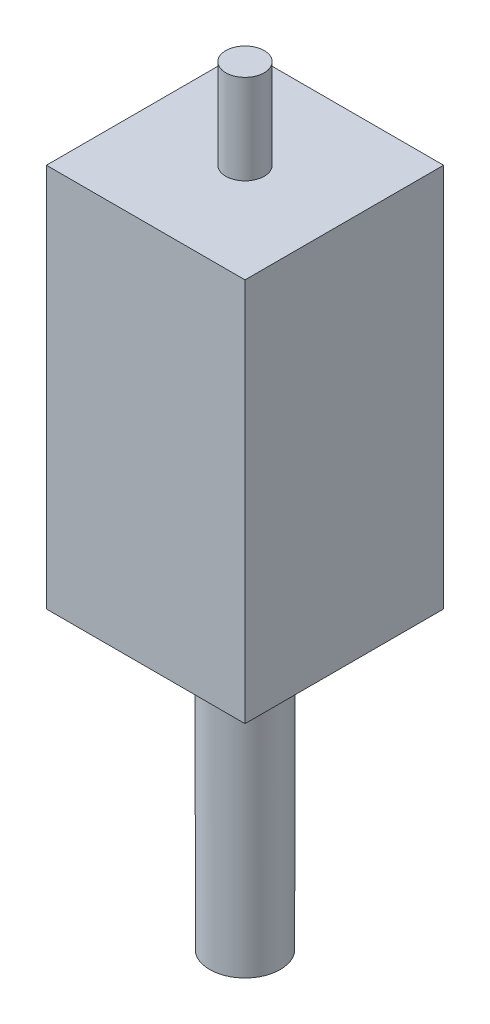
SolidWorks part; units mm, degrees
ref_plane "Front" through (0, 0, 0) normal (0, 0, 1) x (1, 0, 0)
ref_plane "Top" through (0, 0, 0) normal (0, 1, 0) x (1, 0, 0)
ref_plane "Right" through (0, 0, 0) normal (1, 0, 0) x (0, 0, -1)
sketch "Esboço2" plane through (0, 0, 0) normal (0, 0, 1) x (1, 0, 0)
  line L0 (6.8703, 15.805) -> (6.8703, -14.195) construction
  line L1 (-0.8797, 15.805) -> (14.6203, 15.805)
  line L2 (-0.8797, 15.805) -> (-0.8797, -14.195)
  line L3 (-0.8797, -14.195) -> (14.6203, -14.195)
  line L4 (14.6203, 15.805) -> (14.6203, -14.195)
  line L5 (6.8703, -14.195) -> (6.8703, -37.195) construction
  line L6 (6.8703, 15.805) -> (6.8703, 22.805) construction
  dimension "D1" = 15.5
  dimension "D2" = 30
extrude "Ressalto-extrusão1" add sketch "Esboço2" along normal blind 15.5
sketch "Esboço3" plane through (0, 15.805, 0) normal (0, 1, 0) x (1, 0, 0)
  line L0 (14.6203, 0) -> (-0.8797, -15.5) construction
  circle A0 centre (6.8703, -7.75) radius 1.5
extrude "Ressalto-extrusão2" add sketch "Esboço3" along normal blind 7
sketch "Esboço4" plane through (0, -14.195, 0) normal (0, -1, 0) x (1, 0, 0)
  line L0 (14.6203, 15.5) -> (-0.8797, 0) construction
  circle A0 centre (6.8703, 7.75) radius 2.75
extrude "Ressalto-extrusão3" add sketch "Esboço4" along normal blind 23
sketch "Esboço7" plane through (-0.8797, 0, 0) normal (-1, 0, 0) x (0, 0, 1)
  line L0 (7.75, 15.805) -> (7.75, -14.195) construction
  line L1 (15.5, 15.805) -> (0, 15.805) construction
  line L2 (15.5, -14.195) -> (0, -14.195) construction
  line L3 (7.75, -6.695) -> (7.75, 8.305)
  point P6 (0, 0)
  point P9 (7.75, 0.805)
  point P10 (0, 0)
  dimension "D1" = 15
hole_wizard "Broca de rosquear para tarraxa de M31" positions "3DSketch1" profile "Esboço8" hole size "M3" standard "ISO"
sketch3d "3DSketch1"
  point P0 (-0.8797, 8.305, 7.75)
  point P3 (-0.8797, -6.695, 7.75)
sketch "Esboço8" plane through (-0.8797, 8.305, 7.75) normal (0, 1, 0) x (0, 0, 1)
  line L0 (0, 0) -> (0, 1.8511)
  line L1 (0, 1.8511) -> (1.25, 1.1)
  line L2 (1.25, 1.1) -> (1.25, 0)
  line L5 (1.25, 0) -> (0, 0)
  line L10 (0, 1.8511) -> (-1.25, 1.1) construction
  line L11 (0, -6.35) -> (0, 107.95) construction
  dimension "Hole Dia." = 2.5
  dimension "Hole Depth" = 1.1
  dimension "Drill Angle" = 118
